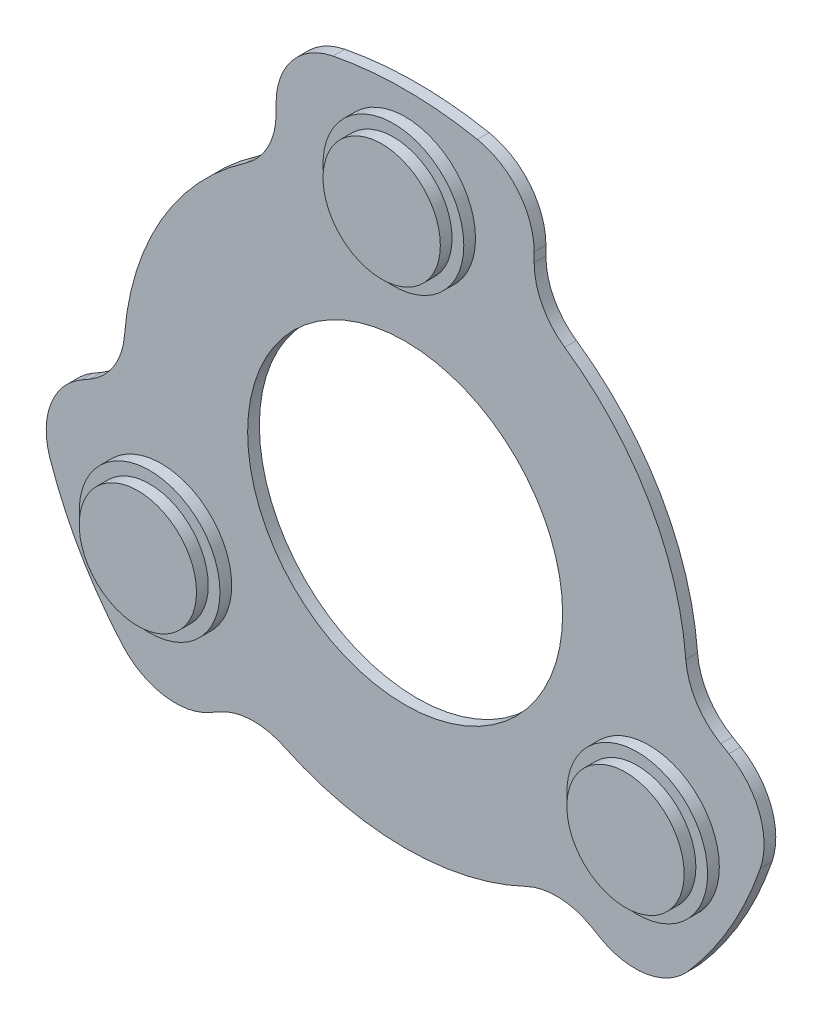
SolidWorks part; units mm, degrees
material "Silicon"
ref_plane "Front Plane" through (0, 0, 0) normal (0, 0, 1) x (1, 0, 0)
ref_plane "Top Plane" through (0, 0, 0) normal (0, 1, 0) x (1, 0, 0)
ref_plane "Right Plane" through (0, 0, 0) normal (1, 0, 0) x (0, 0, -1)
sketch "Sketch9" plane through (0, 0, 0) normal (0, 0, 1) x (1, 0, 0)
  line L0 (0, 0) -> (0, 36.4445)
  line L1 (-11, 30.05) -> (-11, 21.3307)
  line L2 (11, 30.05) -> (11, 21.3307)
  line L3 (20.524, -24.5513) -> (12.973, -20.1916)
  line L4 (31.524, -5.4987) -> (23.973, -1.1391)
  line L5 (-31.524, -5.4987) -> (-23.973, -1.1391)
  line L6 (-20.524, -24.5513) -> (-12.973, -20.1916)
  circle A0 centre (0, 0) radius 13.4273
  arc A1 (-12.973, -20.1916) -> (12.973, -20.1916) centre (0, 0) ccw
  arc A2 (-31.524, -5.4987) -> (-20.524, -24.5513) centre (0, 0) ccw
  circle A3 centre (0, 24) radius 5
  arc A4 (-31.524, -5.4987) -> (-20.524, -24.5513) centre (0, 0) ccw
  arc A5 (-12.973, -20.1916) -> (12.973, -20.1916) centre (0, 0) ccw
  circle A6 centre (20.7846, -12) radius 5
  arc A7 (-31.524, -5.4987) -> (-20.524, -24.5513) centre (0, 0) ccw
  arc A8 (-12.973, -20.1916) -> (12.973, -20.1916) centre (0, 0) ccw
  circle A9 centre (-20.7846, -12) radius 5
  arc A10 (11, 30.05) -> (-11, 30.05) centre (0, 0) ccw
  arc A11 (20.524, -24.5513) -> (31.524, -5.4987) centre (0, 0) ccw
  arc A12 (20.524, -24.5513) -> (31.524, -5.4987) centre (0, 0) ccw
  arc A13 (20.524, -24.5513) -> (31.524, -5.4987) centre (0, 0) ccw
  arc A14 (23.973, -1.1391) -> (11, 21.3307) centre (0, 0) ccw
  arc A15 (23.973, -1.1391) -> (11, 21.3307) centre (0, 0) ccw
  arc A16 (23.973, -1.1391) -> (11, 21.3307) centre (0, 0) ccw
  arc A17 (11, 30.05) -> (-11, 30.05) centre (0, 0) ccw
  arc A18 (11, 30.05) -> (-11, 30.05) centre (0, 0) ccw
  arc A19 (-11, 21.3307) -> (-23.973, -1.1391) centre (0, 0) ccw
  arc A20 (-11, 21.3307) -> (-23.973, -1.1391) centre (0, 0) ccw
  arc A21 (-11, 21.3307) -> (-23.973, -1.1391) centre (0, 0) ccw
  point P30 (0, 0)
  dimension "D1" = 11
  dimension "D3" = 3
  dimension "D5" = 10
  dimension "D2" = 11
  dimension "D4" = 24
extrude "Boss-Extrude1" add sketch "Sketch9" along normal blind 1
fillet "Fillet1" radius 6 12 edges at (11, 21.3307, 0.5) (11, 30.05, 0.5) (31.524, -5.4987, 0.5) (23.973, -1.1391, 0.5) (20.524, -24.5513, 0.5) (12.973, -20.1916, 0.5) (-12.973, -20.1916, 0.5) (-20.524, -24.5513, 0.5) (-23.973, -1.1391, 0.5) (-31.524, -5.4987, 0.5) (-11, 21.3307, 0.5) (-11, 30.05, 0.5)
sketch "Sketch14" plane through (0, 0, 1) normal (0, 0, 1) x (1, 0, 0)
  circle A0 centre (0, 24) radius 5
  circle A1 centre (0, 24) radius 6
extrude "Boss-Extrude2" add sketch "Sketch14" along normal blind 2 and the other way blind 3 contours A0
sketch "Sketch15" plane through (0, 0, 1) normal (0, 0, 1) x (1, 0, 0)
  circle A0 centre (0, 24) radius 6
extrude "Boss-Extrude3" add sketch "Sketch15" along normal blind 1 and the other way blind 2
pattern_circular "CirPattern1" count 3 over 360 about axis through (0, 0, 0) along (0, 0, 1) of "Boss-Extrude3", "Boss-Extrude2"
